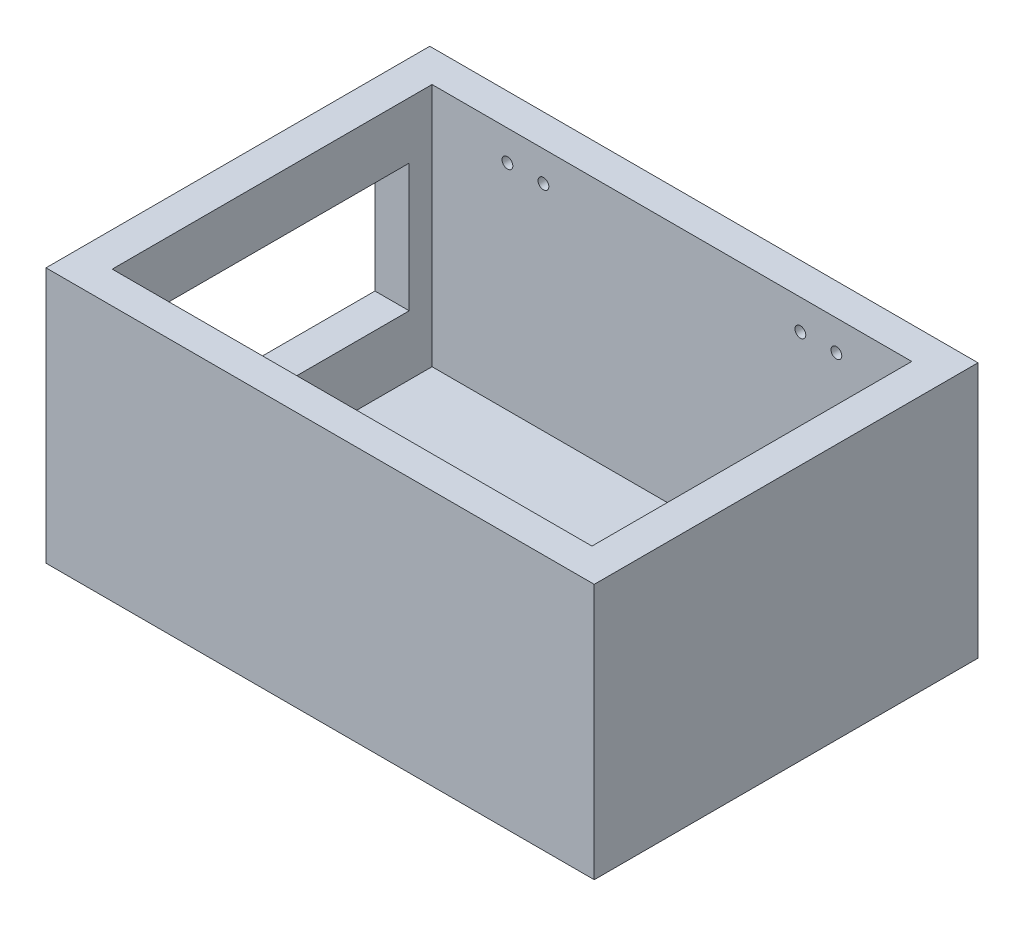
SolidWorks part; units mm, degrees
ref_plane "Front Plane" through (0, 0, 0) normal (0, 0, 1) x (1, 0, 0)
ref_plane "Top Plane" through (0, 0, 0) normal (0, 1, 0) x (1, 0, 0)
ref_plane "Right Plane" through (0, 0, 0) normal (1, 0, 0) x (0, 0, -1)
sketch "Sketch2" plane through (0, 0, 0) normal (0, 1, 0) x (1, 0, 0)
  line L1 (0, 0) -> (152.4, 0)
  line L2 (0, 0) -> (0, -106.68)
  line L3 (0, -106.68) -> (152.4, -106.68)
  line L4 (152.4, 0) -> (152.4, -106.68)
  dimension "D1" = 152.4
  dimension "D2" = 106.68
extrude "Boss-Extrude1" add sketch "Sketch2" along normal blind 71.12
sketch "Sketch3" plane through (0, 71.12, 0) normal (0, 1, 0) x (1, 0, 0)
  line L0 (152.4, -106.68) -> (152.4, 0) construction
  line L1 (142.875, -97.79) -> (9.525, -97.79)
  line L2 (142.875, -97.79) -> (142.875, -8.89)
  line L3 (142.875, -8.89) -> (9.525, -8.89)
  line L4 (9.525, -97.79) -> (9.525, -8.89)
  line L5 (152.4, 0) -> (0, 0) construction
  line L6 (0, -106.68) -> (152.4, -106.68) construction
  line L7 (0, 0) -> (0, -106.68) construction
  dimension "D1" = 9.525
  dimension "D2" = 8.89
  dimension "D3" = 8.89
  dimension "D4" = 9.525
extrude "Cut-Extrude1" cut sketch "Sketch3" against normal blind 67.945 contours L2 L1 L4 L3
sketch "Sketch8" plane through (142.875, 0, 0) normal (-1, 0, 0) x (0, 0, 1)
  line L0 (97.79, 71.12) -> (8.89, 71.12) construction
  line L1 (53.34, 71.12) -> (53.34, 27.94)
  line L2 (53.34, 27.94) -> (42.418, 27.94)
  line L3 (53.34, 27.94) -> (75.438, 27.94)
  line L4 (42.418, 3.175) -> (42.418, 52.705)
  line L5 (75.438, 3.175) -> (75.438, 52.705)
  line L6 (42.418, 52.705) -> (45.72, 52.705)
  line L7 (42.418, 52.705) -> (42.418, 3.175)
  line L8 (42.418, 3.175) -> (45.72, 3.175)
  line L9 (45.72, 52.705) -> (45.72, 3.175)
  line L10 (97.79, 3.175) -> (8.89, 3.175) construction
  line L11 (75.438, 52.705) -> (70.358, 52.705)
  line L12 (75.438, 52.705) -> (75.438, 3.175)
  line L13 (75.438, 3.175) -> (70.358, 3.175)
  line L14 (70.358, 52.705) -> (70.358, 3.175)
  point P9 (42.418, 27.94)
  point P14 (75.438, 27.94)
  dimension "D1" = 43.18
  dimension "D2" = 10.922
  dimension "D3" = 22.098
  dimension "D5" = 3.302
  dimension "D7" = 5.08
extrude "Boss-Extrude2" add sketch "Sketch8" along normal blind 17.272 contours L11 L14 L3 L5 | L3 L14 L13 L5 | L7 L6 L9 L8
sketch "Sketch9" [suppressed] plane through (125.603, 0, 0) normal (-1, 0, 0) x (0, 0, 1)
  line L0 (39.878, 3.175) -> (43.18, 3.175) construction
  line L2 (67.818, 3.175) -> (72.898, 3.175) construction
  line L4 (41.402, 34.925) -> (39.878, 34.925) construction
  line L7 (39.878, 52.705) -> (39.878, 3.175) construction
  line L12 (71.374, 34.925) -> (72.898, 34.925) construction
  line L13 (72.898, 3.175) -> (72.898, 52.705) construction
  circle A0 centre (41.402, 34.925) radius 1.016
  circle A1 centre (71.374, 34.925) radius 1.016
  point P17 (41.402, 34.925)
  point P22 (71.374, 34.925)
  dimension "D1" = 2.032
  dimension "D2" = 2.032
  dimension "D5" = 1.524
  dimension "D3" = 31.75
  dimension "D4" = 31.75
  dimension "D6" = 1.524
extrude "Cut-Extrude2" [suppressed] cut sketch "Sketch9" against normal blind 2.032 contours A0 | A1
sketch "Sketch12" plane through (0, 0, 0) normal (-1, 0, 0) x (0, 0, 1)
  line L0 (0, 0) -> (106.68, 0) construction
  line L1 (15.24, 55.372) -> (91.44, 55.372)
  line L2 (15.24, 55.372) -> (15.24, 19.812)
  line L3 (15.24, 19.812) -> (91.44, 19.812)
  line L4 (91.44, 55.372) -> (91.44, 19.812)
  point P6 (53.34, 19.812)
  point P7 (53.34, 0)
  dimension "D1" = 76.2
  dimension "D2" = 35.56
  dimension "D3" = 19.812
extrude "Cut-Extrude3" cut sketch "Sketch12" against normal blind 9.525 contours L2 L1 L4 L3
sketch "Sketch14" plane through (0, 0, 97.79) normal (0, 0, -1) x (-1, 0, 0)
  line L3 (-85.217, 3.175) -> (-9.525, 3.175)
  line L4 (-9.525, 25.527) -> (-9.525, 3.175)
  line L9 (-85.217, 3.175) -> (-85.217, 25.908)
  line L12 (-9.525, 22.86) -> (-83.566, 22.86)
  line L13 (-83.566, 25.908) -> (-83.566, 22.86)
  line L14 (-142.875, 3.175) -> (-9.525, 3.175) construction
  line L18 (-9.525, 3.175) -> (-9.525, 71.12) construction
  line L19 (-83.566, 25.908) -> (-85.217, 25.908)
  dimension "D1" = 19.685
  dimension "D2" = 3.048
  dimension "D4" = 75.692
  dimension "D5" = 1.651
extrude "Boss-Extrude3" [suppressed] add sketch "Sketch14" along normal blind 6.35
sketch "Sketch32" plane through (0, 0, 42.418) normal (0, 0, -1) x (-1, 0, 0)
  line L0 (-125.603, 52.705) -> (-125.603, 3.175) construction
  line L1 (-142.875, 52.705) -> (-125.603, 52.705)
  line L2 (-142.875, 52.705) -> (-142.875, 41.275)
  line L3 (-142.875, 41.275) -> (-125.603, 41.275)
  line L4 (-125.603, 52.705) -> (-125.603, 41.275)
  dimension "D1" = 11.43
extrude "Cut-Extrude10" [suppressed] cut sketch "Sketch32" against normal blind 33.02
sketch "Sketch35" plane through (0, 0, 8.89) normal (0, 0, 1) x (1, 0, 0)
  line L0 (9.525, 62.738) -> (30.48, 62.738) construction
  line L1 (9.525, 3.175) -> (9.525, 71.12) construction
  line L2 (142.875, 62.738) -> (121.92, 62.738) construction
  line L3 (142.875, 3.175) -> (142.875, 71.12) construction
  line L4 (30.48, 62.738) -> (40.4876, 62.738) construction
  line L5 (121.92, 62.738) -> (111.9124, 62.738) construction
  line L6 (142.875, 71.12) -> (9.525, 71.12) construction
  line L9 (0, 71.12) -> (0, 0) construction
  circle A0 centre (30.48, 62.738) radius 1.4986
  circle A1 centre (40.4876, 62.738) radius 1.4986
  circle A2 centre (111.9124, 62.738) radius 1.4986
  circle A3 centre (121.92, 62.738) radius 1.4986
  dimension "D5" = 2.9972
  dimension "D6" = 2.9972
  dimension "D7" = 2.9972
  dimension "D8" = 2.9972
  dimension "D1" = 30.48
  dimension "D2" = 10.0076
  dimension "D3" = 10.0076
  dimension "D4" = 8.382
extrude "Cut-Extrude12" cut sketch "Sketch35" against normal blind 4.46 and the other way blind 93.82
sketch "Sketch36" plane through (0, 0, 0) normal (-1, 0, 0) x (0, 0, 1)
  line L0 (0, 63.2214) -> (106.68, 63.2214) construction
  line L1 (0, 71.12) -> (0, 0) construction
  line L2 (106.68, 71.12) -> (106.68, 0) construction
  circle A0 centre (53.34, 63.2214) radius 1.905
  dimension "D1" = 3.81
extrude "Cut-Extrude13" cut sketch "Sketch36" against normal blind 2.54
sketch "Sketch37" plane through (0, 0, 0) normal (-1, 0, 0) x (0, 0, 1)
  line L1 (67.31, 5.842) -> (78.74, 5.842)
  line L2 (67.31, 5.842) -> (67.31, 17.272)
  line L3 (67.31, 17.272) -> (78.74, 17.272)
  line L4 (78.74, 5.842) -> (78.74, 17.272)
  line L5 (106.68, 71.12) -> (106.68, 0) construction
  line L6 (15.24, 19.812) -> (91.44, 19.812) construction
  dimension "D1" = 27.94
  dimension "D2" = 2.54
  dimension "D3" = 11.43
  dimension "D4" = 11.43
extrude "Cut-Extrude14" cut sketch "Sketch37" against normal blind 9.525
